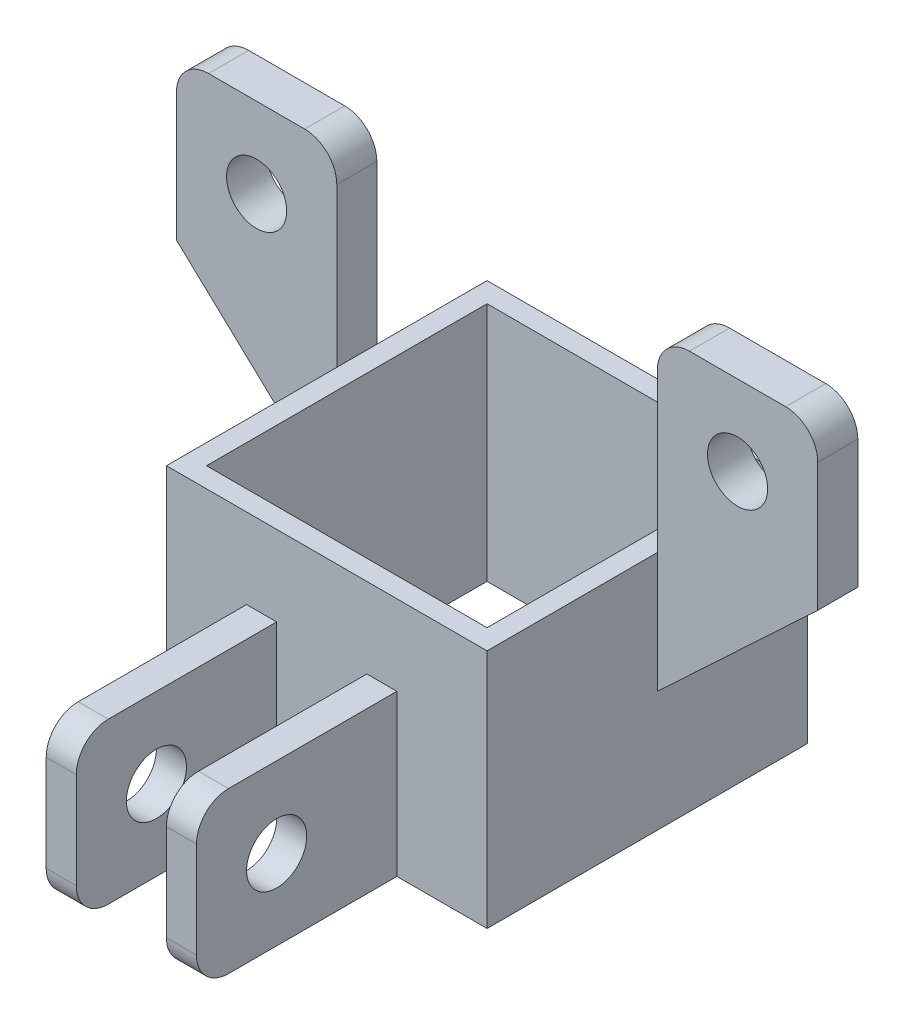
SolidWorks part; units mm, degrees
material "Alloy Steel"
ref_plane "Front Plane" through (0, 0, 0) normal (0, 0, 1) x (1, 0, 0)
ref_plane "Top Plane" through (0, 0, 0) normal (0, 1, 0) x (1, 0, 0)
ref_plane "Right Plane" through (0, 0, 0) normal (1, 0, 0) x (0, 0, -1)
other "Configuration Table"
sketch "Sketch2" plane through (0, 0, 0) normal (0, 0, 1) x (1, 0, 0)
  line L1 (0, 0) -> (50.8, 0)
  line L2 (0, 0) -> (0, 38.1)
  line L3 (0, 38.1) -> (50.8, 38.1)
  line L4 (50.8, 0) -> (50.8, 38.1)
  dimension "D1" = 38.1
  dimension "D2" = 50.8
extrude "Boss-Extrude1" add sketch "Sketch2" against normal blind 50.8
sketch "Sketch5" plane through (0, 38.1, 0) normal (0, 1, 0) x (1, 0, 0)
  line L0 (0, 50.8) -> (0, 0) construction
  line L1 (3.175, 3.175) -> (47.625, 3.175)
  line L2 (3.175, 3.175) -> (3.175, 47.625)
  line L3 (3.175, 47.625) -> (47.625, 47.625)
  line L4 (47.625, 3.175) -> (47.625, 47.625)
  line L5 (50.8, 0) -> (0, 0) construction
  line L6 (50.8, 50.8) -> (50.8, 0) construction
  line L7 (50.8, 50.8) -> (0, 50.8) construction
  dimension "D1" = 3.175
  dimension "D2" = 3.175
  dimension "D3" = 3.175
  dimension "D4" = 3.175
extrude "Cut-Extrude3" cut sketch "Sketch5" against normal through all
sketch "Sketch7" plane through (0, 0, 0) normal (0, 0, 1) x (1, 0, 0)
  line L0 (0, 0) -> (50.8, 0) construction
  line L1 (12.7, 0) -> (17.4625, 0)
  line L2 (12.7, 0) -> (12.7, 25.4)
  line L3 (12.7, 25.4) -> (17.4625, 25.4)
  line L4 (17.4625, 0) -> (17.4625, 25.4)
  line L5 (0, 38.1) -> (0, 0) construction
  line L7 (31.75, 0) -> (36.5125, 0)
  line L8 (31.75, 0) -> (31.75, 25.4)
  line L9 (31.75, 25.4) -> (36.5125, 25.4)
  line L10 (36.5125, 0) -> (36.5125, 25.4)
  dimension "D1" = 25.4
  dimension "D2" = 4.7625
  dimension "D3" = 12.7
  dimension "D4" = 4.7625
  dimension "D5" = 14.2875
extrude "Boss-Extrude2" add sketch "Sketch7" along normal blind 31.75
fillet "Fillet1" radius 5.08 4 edges at (34.1312, 0, 31.75) (15.0812, 0, 31.75) (15.0812, 25.4, 31.75) (34.1312, 25.4, 31.75)
sketch "Sketch8" plane through (36.5125, 0, 0) normal (1, 0, 0) x (0, 0, -1)
  line L0 (-31.75, 5.08) -> (-31.75, 20.32) construction
  line L1 (-26.67, 25.4) -> (0, 25.4) construction
  circle A0 centre (-19.05, 12.7) radius 4.7625
  dimension "D1" = 9.525
  dimension "D2" = 12.7
  dimension "D3" = 12.7
extrude "Cut-Extrude4" cut sketch "Sketch8" against normal through all
ref_plane "Plane1" through (0, 0, -33.3375) normal (0, 0, -1) x (-1, 0, 0)
sketch "Sketch9" plane through (0, 0, -33.3375) normal (0, 0, -1) x (-1, 0, 0)
  line L0 (0, 38.1) -> (0, 68.2625)
  line L1 (0, 68.2625) -> (25.4, 68.2625)
  line L2 (25.4, 68.2625) -> (25.4, 42.8625)
  line L3 (25.4, 42.8625) -> (0, 19.05)
  line L4 (0, 38.1) -> (0, 0) construction
  line L5 (0, 19.05) -> (0, 38.1)
  line L6 (-50.8, 38.1) -> (0, 38.1) construction
  line L7 (-25.4, 38.1) -> (-25.4, 0) construction
  line L9 (-17.4625, 0) -> (-31.75, 0) construction
  line L10 (-76.2, 42.8625) -> (-50.8, 19.05)
  line L11 (-76.2, 68.2625) -> (-76.2, 42.8625)
  line L12 (-50.8, 68.2625) -> (-76.2, 68.2625)
  line L13 (-50.8, 38.1) -> (-50.8, 68.2625)
  line L14 (-50.8, 19.05) -> (-50.8, 38.1)
  dimension "D1" = 25.4
  dimension "D2" = 30.1625
  dimension "D3" = 25.4
  dimension "D4" = 19.05
ref_plane "Plane2" through (25.4, 0, 0) normal (1, 0, 0) x (0, 0, -1)
extrude "Boss-Extrude3" add sketch "Sketch9" against normal blind 6.35
sketch "Sketch10" plane through (0, 0, -26.9875) normal (0, 0, 1) x (1, 0, 0)
  line L0 (-25.4, 42.8625) -> (-25.4, 68.2625) construction
  line L1 (-25.4, 68.2625) -> (0, 68.2625) construction
  line L2 (25.4, 38.1) -> (25.4, 0) construction
  line L3 (50.8, 38.1) -> (0, 38.1) construction
  line L4 (17.4625, 0) -> (31.75, 0) construction
  circle A0 centre (-12.7, 55.5625) radius 4.7625
  circle A1 centre (63.5, 55.5625) radius 4.7625
  dimension "D1" = 9.525
  dimension "D2" = 12.7
  dimension "D3" = 12.7
extrude "Cut-Extrude5" cut sketch "Sketch10" against normal through all
fillet "Fillet2" radius 5.08 4 edges at (-25.4, 68.2625, -30.1625) (0, 68.2625, -30.1625) (50.8, 68.2625, -30.1625) (76.2, 68.2625, -30.1625)
